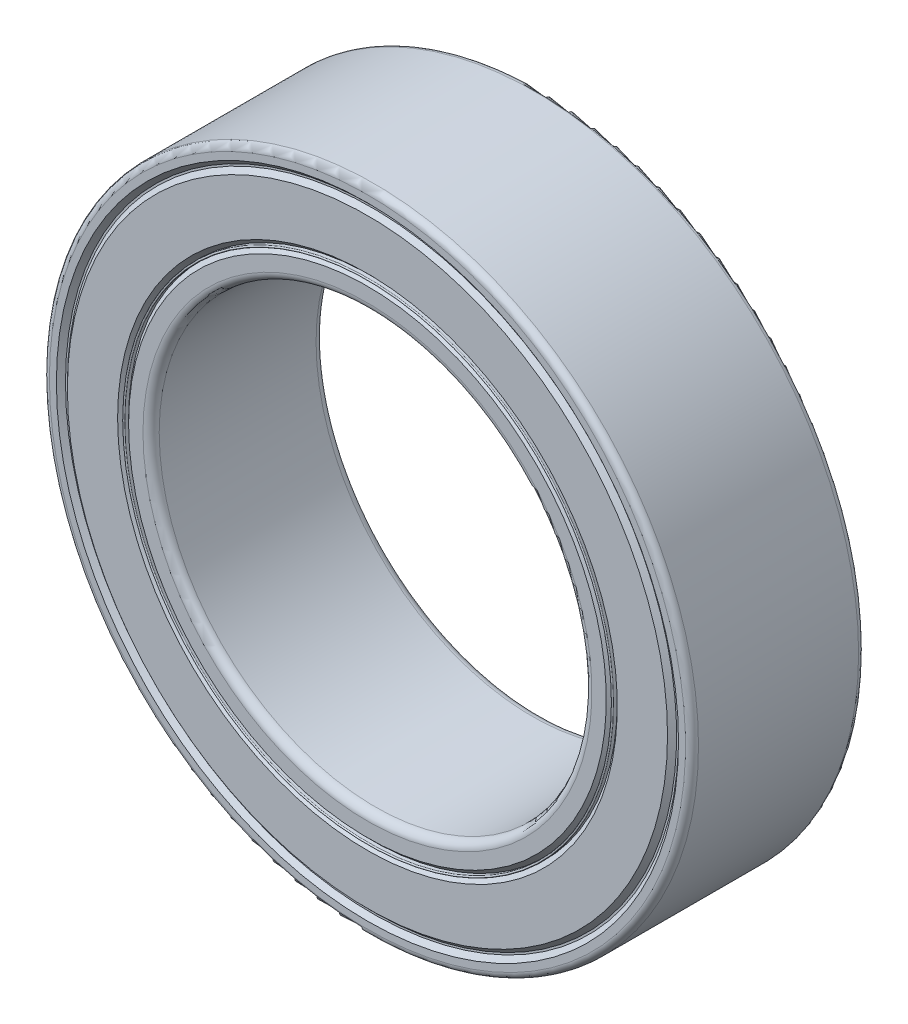
SolidWorks part; units mm, degrees
ref_plane "Front Plane" through (0, 0, 0) normal (0, 0, 1) x (1, 0, 0)
ref_plane "Top Plane" through (0, 0, 0) normal (0, 1, 0) x (1, 0, 0)
ref_plane "Right Plane" through (0, 0, 0) normal (1, 0, 0) x (0, 0, -1)
sketch "Sketch1" plane through (0, 0, 0) normal (0, 0, 1) x (1, 0, 0)
  line L0 (0, 6.25) -> (0, 7.5) construction
  line L1 (0, 5) -> (0, 6.25) construction
  line L2 (0, 7.5) -> (0, 7.0833) construction
  line L3 (0, 7.0833) -> (0, 6.6667) construction
  line L4 (0, 6.6667) -> (0, 6.25) construction
  circle A0 centre (0, 0) radius 5
  circle A1 centre (0, 0) radius 7.5
  circle A2 centre (0, 0) radius 7.0833 construction
  circle A4 centre (0, 0) radius 5.625 construction
  point P6 (0, 5.625)
  dimension "OD" = 15
  dimension "ID" = 10
sketch "Sketch2" plane through (0, 0, 0) normal (1, 0, 0) x (0, 0, -1)
  line L0 (-2, 7.5) -> (2, 7.5) construction
  line L1 (-2, 5) -> (-2, -5) construction
  line L2 (2, 7.5) -> (2, -7.5) construction
  line L3 (2, 0) -> (-2, 0) construction
  dimension "Width" = 4
  dimension "For Shaft Diameter" = 10
  dimension "For Housing ID" = 15
sketch "Sketch3" plane through (0, 0, 0) normal (1, 0, 0) x (0, 0, -1)
  line L0 (-2, -7.5) -> (2, -7.5)
  line L1 (2, -7.5) -> (2, -7.0833)
  line L2 (2, -7.0833) -> (-2, -7.0833)
  line L3 (-2, -7.0833) -> (-2, -7.5)
  line L4 (-2, 7.5) -> (2, 7.5) construction
  line L6 (-2, -5) -> (2, -5)
  line L9 (-2, -5.625) -> (2, -5.625)
  line L12 (-2, -5.625) -> (-2, -5)
  line L13 (2, -5.625) -> (2, -5)
  line L14 (-2, 0) -> (2, 0) construction
  point P6 (0, -7.0833)
  point P7 (0, -5.625)
  point P8 (0, -5)
  point P20 (0, -7.5)
  dimension "D1" = 1.4583
revolve "Revolve1" add sketch "Sketch3" angle 360 about L3
sketch "Sketch4" plane through (0, 0, 0) normal (1, 0, 0) x (0, 0, -1)
  line L0 (0, 7.5) -> (0, -7.5) construction
  line L1 (-2, -5.625) -> (-2, -7.0833) construction
  circle A0 centre (0, -6.3542) radius 0.875
  point P8 (-2, -6.3542)
  dimension "D1" = 1.75
revolve "Cut-Revolve1" cut sketch "Sketch4" angle 360 about L3
sketch "Sketch5" plane through (0, 0, 0) normal (1, 0, 0) x (0, 0, -1)
  line L0 (0, -5.4792) -> (0, -7.2292)
  line L1 (0, 7.5) -> (0, -7.5) construction
  circle A0 centre (0, -6.3542) radius 0.875 construction
  arc A1 (0, -5.4792) -> (0, -7.2292) centre (0, -6.3542) cw
revolve "Revolve2" add sketch "Sketch5" angle 360 about L0
pattern_circular "CirPattern1" count 15 over 360 about axis through (0, 0, 0) along (0, 0, 1) of bodies 138
fillet "Fillet1" radius 0.15 2 edges at (-7.5, 0, -2) (-7.5, 0, 2)
fillet "Fillet2" radius 0.1875 2 edges at (-5, 0, -2) (-5, 0, 2)
chamfer "Chamfer1" distance 0.105 angle 45 2 edges at (-7.0833, 0, -2) (-7.0833, 0, 2)
chamfer "Chamfer2" distance 0.105 angle 45 2 edges at (-5.625, 0, -2) (-5.625, 0, 2)
sketch "Sketch6" plane through (0, 0, 0) normal (1, 0, 0) x (0, 0, -1)
  line L0 (-2, -5.7738) -> (-2, -6.9346)
  line L1 (-2, -6.9346) -> (-1.895, -7.0396)
  line L2 (-1.895, -7.0396) -> (-1.895, -7.0833)
  line L3 (-2, -5.7738) -> (-1.895, -5.6688)
  line L4 (-1.895, -5.6688) -> (-1.895, -5.625)
  line L5 (-1.895, 7.0833) -> (-1.895, -7.0833) construction
  line L6 (-1.895, -7.0833) -> (-0.875, -7.0833)
  line L7 (-0.875, -7.0833) -> (-0.875, -5.625)
  line L8 (-0.875, -5.625) -> (-1.895, -5.625)
  line L9 (0, 0) -> (0, 7.5) construction
  line L10 (1.895, -7.0833) -> (0.875, -7.0833)
  line L11 (1.895, -7.0396) -> (1.895, -7.0833)
  line L12 (2, -6.9346) -> (1.895, -7.0396)
  line L13 (2, -5.7738) -> (2, -6.9346)
  line L14 (2, -5.7738) -> (1.895, -5.6688)
  line L15 (1.895, -5.6688) -> (1.895, -5.625)
  line L16 (0.875, -5.625) -> (1.895, -5.625)
  line L17 (0.875, -7.0833) -> (0.875, -5.625)
  circle A0 centre (0, -6.3542) radius 0.875 construction
  dimension "D1" = 45
  dimension "D2" = 45
  dimension "D3" = 0.0438
revolve "Revolve3" add sketch "Sketch6" angle 360 about L3
sketch "Sketch7" plane through (0, 0, 0) normal (1, 0, 0) x (0, 0, -1)
  line L0 (-1.895, -5.6688) -> (-1.895, -5.625)
  line L1 (-1.895, -5.625) -> (-1.9781, -5.625)
  line L2 (-1.9781, -5.6688) -> (-1.895, -5.6688)
  line L3 (-2, -5.7738) -> (-2, -5.625) construction
  line L4 (0, 7.5) -> (0, 0) construction
  line L5 (1.895, -5.625) -> (1.9781, -5.625)
  line L6 (1.895, -5.6688) -> (1.895, -5.625)
  line L7 (1.9781, -5.6688) -> (1.895, -5.6688)
  arc A0 (-1.9781, -5.625) -> (-1.9781, -5.6688) centre (-1.9781, -5.6469) ccw
  arc A1 (1.9781, -5.625) -> (1.9781, -5.6688) centre (1.9781, -5.6469) cw
revolve "Revolve4" add sketch "Sketch7" angle 360 about L3
equation "\"D1@Sketch4\"=\"D1@Sketch3\"*1.2"
equation "\"D1@Fillet1\"=\"OD@Sketch1\"*0.01"
equation "\"D1@Fillet2\"=\"D1@Fillet1\"*1.25"
equation "\"D1@Chamfer1\"=\"D1@Fillet1\" * 0.7"
equation "\"D1@Chamfer2\"=\"D1@Chamfer1\""
equation "\"D3@Sketch6\"=\"D1@Sketch3\"*0.03"
equation "\"D1@CirPattern1\"=( pi * \"OD@Sketch1\" )  * .5625 / \"D1@Sketch4\""
